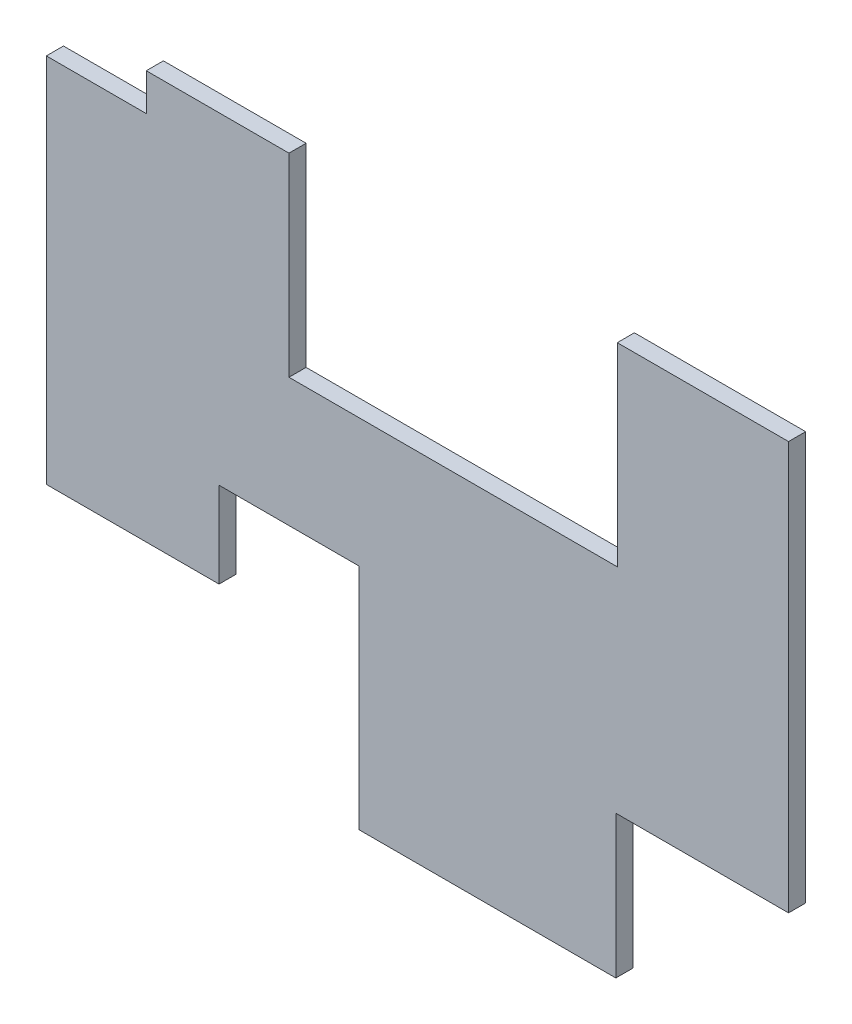
SolidWorks part; units mm, degrees
ref_plane "Plano frontal" through (0, 0, 0) normal (0, 0, 1) x (1, 0, 0)
ref_plane "Plano superior" through (0, 0, 0) normal (0, 1, 0) x (1, 0, 0)
ref_plane "Plano direito" through (0, 0, 0) normal (1, 0, 0) x (0, 0, -1)
sketch "Esboço1" plane through (0, 0, 0) normal (0, 0, 1) x (1, 0, 0)
  line L0 (-45, 96.5) -> (-45, 28.5)
  line L1 (-130, -96.5) -> (130, -96.5)
  line L2 (-130, -96.5) -> (-130, 96.5)
  line L3 (-130, 96.5) -> (130, 96.5)
  line L4 (130, -96.5) -> (130, 96.5)
  line L5 (-130, -96.5) -> (130, 96.5) construction
  line L6 (-130, 96.5) -> (130, -96.5) construction
  line L7 (-45, 28.5) -> (70, 28.5)
  line L8 (-69.5, -16.5) -> (-20.5, -16.5)
  line L9 (-20.5, -16.5) -> (-20.5, -96.5)
  line L10 (0, 0) -> (0, 96.5) construction
  line L11 (69.5, -146.5) -> (69.5, -46.5)
  line L12 (69.5, -46.5) -> (130, -46.5)
  line L13 (70, 96.5) -> (70, 28.5)
  line L14 (-130, 83.5) -> (-95, 83.5)
  line L15 (-95, 83.5) -> (-95, 96.5)
  line L16 (-69.5, -16.5) -> (-69.5, -46.5)
  line L17 (-69.5, -46.5) -> (-130, -46.5)
  point P0 (0, 0)
  point P22 (0, 0)
  point P25 (-71.6975, -46.5)
  dimension "D1" = 260
  dimension "D2" = 50
  dimension "D3" = 125
  dimension "D4" = 85
  dimension "D5" = 193
  dimension "D6" = 100
  dimension "D7" = 60.5
  dimension "D8" = 90
  dimension "D9" = 80
  dimension "D10" = 60
  dimension "D11" = 35
  dimension "D12" = 180
extrude "Ressalto-extrusão1" add sketch "Esboço1" along normal blind 6
